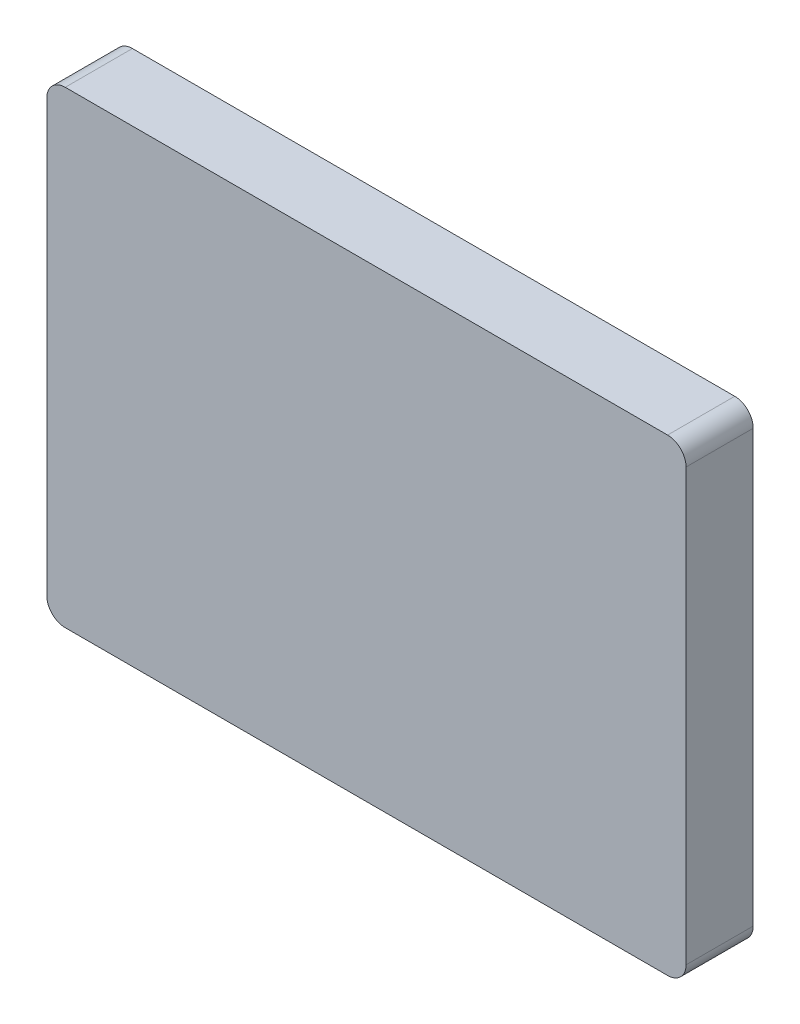
SolidWorks part; units mm, degrees
ref_plane "Front Plane" through (0, 0, 0) normal (0, 0, 1) x (1, 0, 0)
ref_plane "Top Plane" through (0, 0, 0) normal (0, 1, 0) x (1, 0, 0)
ref_plane "Right Plane" through (0, 0, 0) normal (1, 0, 0) x (0, 0, -1)
sketch "Sketch2" plane through (0, 0, 0) normal (0, 0, 1) x (1, 0, 0)
  line L0 (0, -37.2131) -> (0, 23.6883) construction
  line L1 (47.5, 0.1766) -> (-74.8985, 0.1766) construction
  line L7 (-47.6, 32.2766) -> (-47.6, -31.9234)
  line L8 (-44.85, -34.6734) -> (44.85, -34.6734)
  line L9 (47.6, 32.2766) -> (47.6, -31.9234)
  line L13 (44.85, 35.0266) -> (-44.85, 35.0266)
  arc A2 (47.6, 32.2766) -> (44.85, 35.0266) centre (44.85, 32.2766) ccw
  arc A3 (-44.85, 35.0266) -> (-47.6, 32.2766) centre (-44.85, 32.2766) ccw
  arc A6 (-47.6, -31.9234) -> (-44.85, -34.6734) centre (-44.85, -31.9234) ccw
  arc A7 (44.85, -34.6734) -> (47.6, -31.9234) centre (44.85, -31.9234) ccw
  point P3 (0, 0.1766)
  point P5 (0, 0)
  point P8 (0, 0)
  point P10 (0, 0)
  point P21 (0, 0)
  point P22 (0, 0)
  point P23 (0, 0)
  point P24 (-51.8104, -31.2759)
  point P25 (0, 0)
  dimension "D3" = 2.75
  dimension "D1" = 89.7
  dimension "D2" = 64.2
extrude "Boss-Extrude1" add sketch "Sketch2" along normal blind 10
